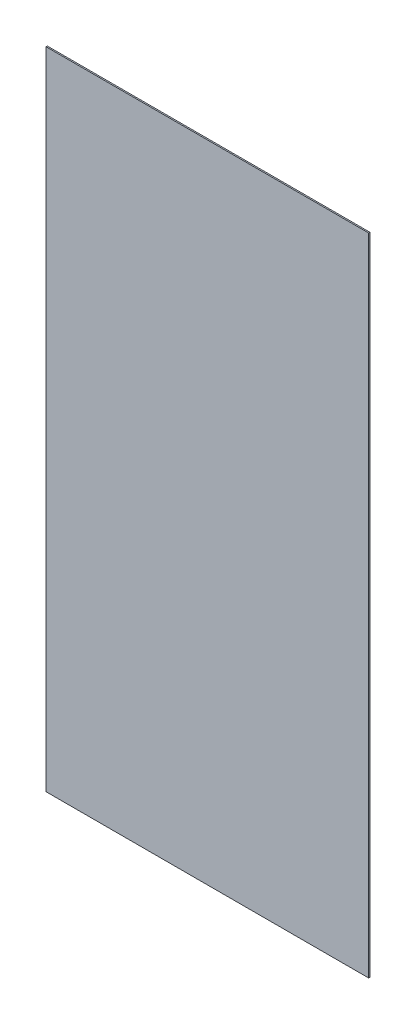
SolidWorks part; units mm, degrees
ref_plane "Front Plane" through (0, 0, 0) normal (0, 0, 1) x (1, 0, 0)
ref_plane "Top Plane" through (0, 0, 0) normal (0, 1, 0) x (1, 0, 0)
ref_plane "Right Plane" through (0, 0, 0) normal (1, 0, 0) x (0, 0, -1)
sketch "Sketch1" plane through (0, 0, 0) normal (0, 0, 1) x (1, 0, 0)
  line L1 (-1250, 2500) -> (1250, 2500)
  line L2 (-1250, 2500) -> (-1250, -2500)
  line L3 (-1250, -2500) -> (1250, -2500)
  line L4 (1250, 2500) -> (1250, -2500)
  line L5 (-1250, 2500) -> (1250, -2500) construction
  line L6 (-1250, -2500) -> (1250, 2500) construction
  point P0 (0, 0)
  dimension "D1" = 5000
  dimension "D2" = 2500
extrude "Boss-Extrude1" add sketch "Sketch1" along normal blind 10
sketch "Sketch2" plane through (0, 0, 0) normal (0, 0, -1) x (-1, 0, 0)
  line L0 (-950, 2500) -> (-950, -2500)
  line L3 (-1250, 2500) -> (1250, 2500) construction
  line L6 (1250, -2500) -> (-1250, -2500) construction
  line L7 (950, 2500) -> (950, -2500)
  line L8 (1250, 2500) -> (1250, -2500) construction
  line L9 (-1250, -2500) -> (-1250, 2500) construction
  dimension "D1" = 300
  dimension "D2" = 300
